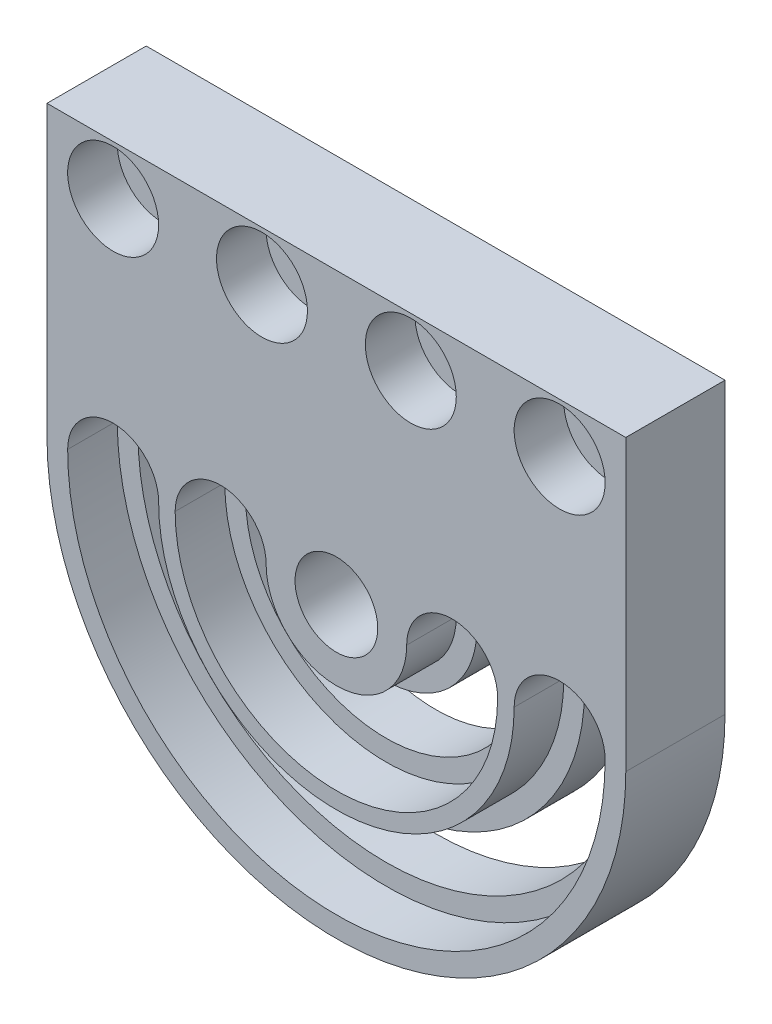
SolidWorks part; units mm, degrees
ref_plane "前视基准面" through (0, 0, 0) normal (0, 0, 1) x (1, 0, 0)
ref_plane "上视基准面" through (0, 0, 0) normal (0, 1, 0) x (1, 0, 0)
ref_plane "右视基准面" through (0, 0, 0) normal (1, 0, 0) x (0, 0, -1)
sketch "草图1" plane through (0, 0, 0) normal (0, 0, 1) x (1, 0, 0)
  line L0 (-35, 0) -> (-35, 35)
  line L1 (-35, 35) -> (35, 35)
  line L2 (35, 35) -> (35, 0)
  line L3 (0, 0) -> (0, -19.951) construction
  arc A0 (-35, 0) -> (35, 0) centre (0, 0) ccw
  circle A1 centre (0, 0) radius 5
  arc A2 (0, 35) -> (-35, 0) centre (0, 0) ccw construction
  arc A3 (35, 0) -> (0, 35) centre (0, 0) ccw construction
  circle A4 centre (-27, 29) radius 3
  circle A5 centre (-9, 29) radius 3
  circle A6 centre (9, 29) radius 3
  circle A7 centre (27, 29) radius 3
  arc A8 (30, 0) -> (24, 0) centre (27, 0) ccw
  arc A15 (17, 0) -> (11, 0) centre (14, 0) ccw
  arc A16 (-30, 0) -> (-24, 0) centre (-27, 0) cw
  arc A17 (-17, 0) -> (-11, 0) centre (-14, 0) cw
  arc A18 (-11, 0) -> (11, 0) centre (0, 0) ccw
  arc A19 (-17, 0) -> (17, 0) centre (0, 0) ccw
  arc A20 (-24, 0) -> (24, 0) centre (0, 0) ccw
  arc A21 (-30, 0) -> (30, 0) centre (0, 0) ccw
  arc A22 (-24, 0) -> (-30, 0) centre (-27, 0) cw construction
  arc A23 (-11, 0) -> (-17, 0) centre (-14, 0) cw construction
  arc A24 (11, 0) -> (17, 0) centre (14, 0) ccw construction
  arc A25 (24, 0) -> (30, 0) centre (27, 0) ccw construction
  dimension "D1" = 70
  dimension "D2" = 10
  dimension "D3" = 6
  dimension "D7" = 8
  dimension "D8" = 6
  dimension "D12" = 11
  dimension "D13" = 180
  dimension "D9" = 6
  dimension "D11" = 180
  dimension "D14" = 17
  dimension "D16" = 180
  dimension "D17" = 24
  dimension "D18" = 180
  dimension "D19" = 30
  dimension "D4" = 6
  dimension "D6" = 8
  dimension "D10" = 13
  dimension "D15" = 18
  dimension "D5" = 4
extrude "凸台-拉伸1" add sketch "草图1" along normal blind 12
sketch "草图2" plane through (0, 0, 12) normal (0, 0, 1) x (1, 0, 0)
  circle A3 centre (-27, 29) radius 5.5
  circle A4 centre (-27, 29) radius 5.5
  circle A6 centre (-9, 29) radius 5.5
  circle A7 centre (-9, 29) radius 5.5
  circle A9 centre (9, 29) radius 5.5
  circle A10 centre (9, 29) radius 5.5
  circle A12 centre (27, 29) radius 5.5
  circle A13 centre (27, 29) radius 5.5
  arc A46 (32.5, 0) -> (21.5, 0) centre (27, 0) ccw
  arc A47 (-32.5, 0) -> (32.5, 0) centre (0, 0) ccw
  arc A48 (-21.5, 0) -> (-32.5, 0) centre (-27, 0) ccw
  arc A49 (-21.5, 0) -> (21.5, 0) centre (0, 0) ccw
  arc A50 (32.5, 0) -> (21.5, 0) centre (27, 0) ccw
  arc A51 (-32.5, 0) -> (32.5, 0) centre (0, 0) ccw
  arc A52 (-21.5, 0) -> (-32.5, 0) centre (-27, 0) ccw
  arc A53 (-21.5, 0) -> (21.5, 0) centre (0, 0) ccw
  arc A64 (19.5, 0) -> (8.5, 0) centre (14, 0) ccw
  arc A65 (-8.5, 0) -> (8.5, 0) centre (0, 0) ccw
  arc A66 (-19.5, 0) -> (19.5, 0) centre (0, 0) ccw
  arc A67 (-8.5, 0) -> (-19.5, 0) centre (-14, 0) ccw
  arc A68 (19.5, 0) -> (8.5, 0) centre (14, 0) ccw
  arc A69 (-8.5, 0) -> (8.5, 0) centre (0, 0) ccw
  arc A70 (-19.5, 0) -> (19.5, 0) centre (0, 0) ccw
  arc A71 (-8.5, 0) -> (-19.5, 0) centre (-14, 0) ccw
  dimension "D1" = 2.5
  dimension "D2" = 2.5
  dimension "D3" = 2.5
  dimension "D4" = 2.5
  dimension "D5" = 2.5
  dimension "D6" = 2.5
extrude "切除-拉伸1" cut sketch "草图2" against normal blind 6
